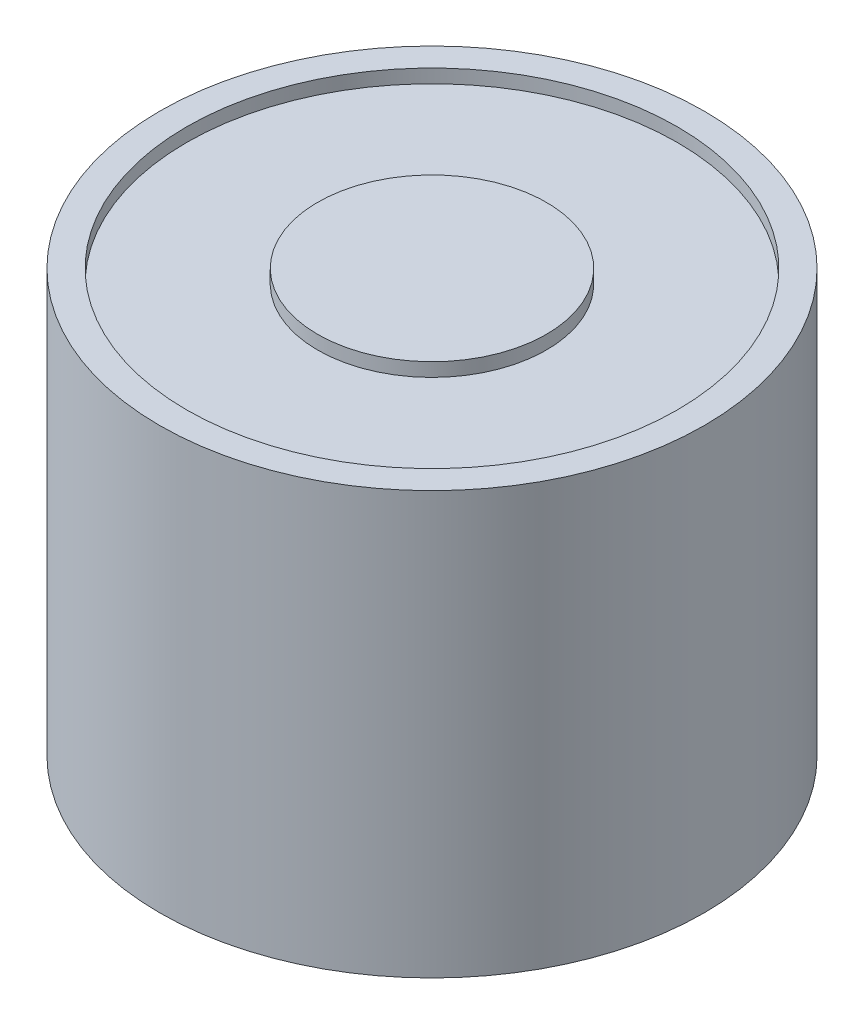
SolidWorks part; units mm, degrees
ref_plane "Front Plane" through (0, 0, 0) normal (0, 0, 1) x (1, 0, 0)
ref_plane "Top Plane" through (0, 0, 0) normal (0, 1, 0) x (1, 0, 0)
ref_plane "Right Plane" through (0, 0, 0) normal (1, 0, 0) x (0, 0, -1)
other "Center of Mass"
sketch "Sketch1" plane through (0, 0, 0) normal (0, 1, 0) x (1, 0, 0)
  circle A0 centre (0, 0) radius 10
  dimension "D1" = 20
extrude "Boss-Extrude1" add sketch "Sketch1" along normal blind 15
sketch "Sketch2" plane through (0, 15, 0) normal (0, 1, 0) x (1, 0, 0)
  circle A0 centre (0, 0) radius 10
  circle A1 centre (0, 0) radius 9.0089
extrude "Boss-Extrude2" add sketch "Sketch2" along normal blind 0.5
sketch "Sketch3" plane through (0, 15, 0) normal (0, 1, 0) x (1, 0, 0)
  circle A0 centre (0, 0) radius 4.2011
extrude "Boss-Extrude3" add sketch "Sketch3" along normal blind 0.5
